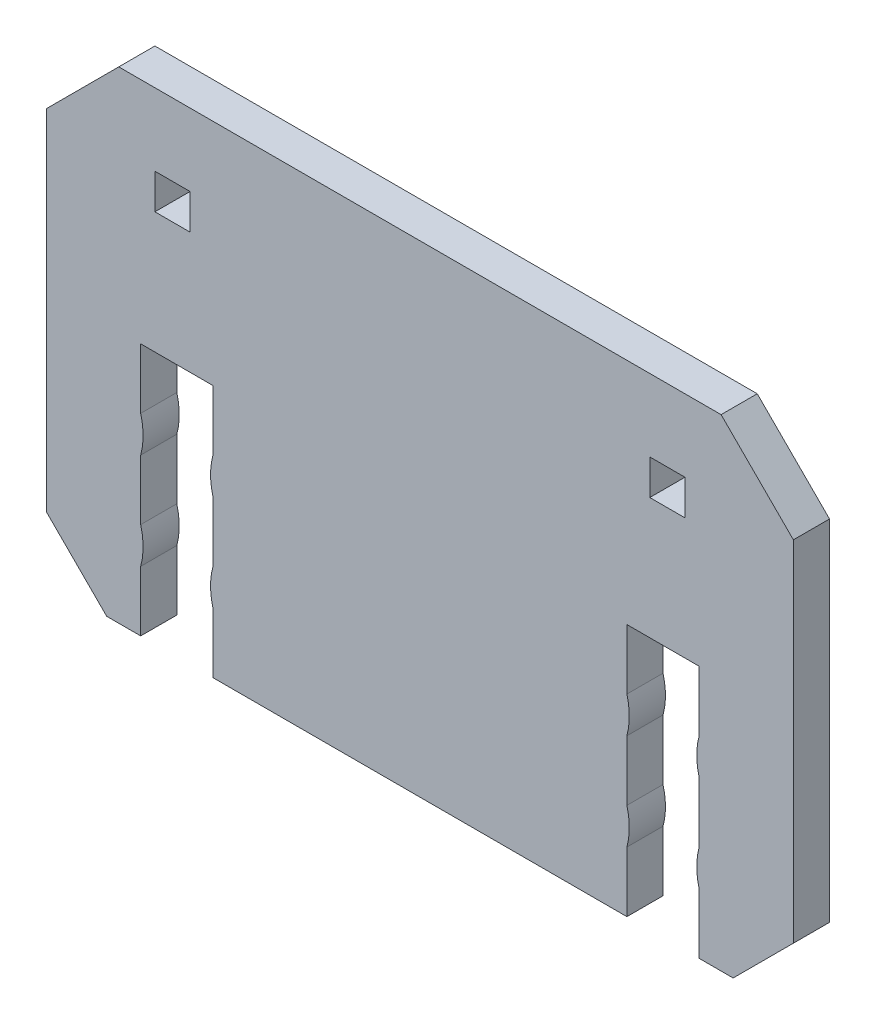
SolidWorks part; units mm, degrees
ref_plane "Front Plane" through (0, 0, 0) normal (0, 0, 1) x (1, 0, 0)
ref_plane "Top Plane" through (0, 0, 0) normal (0, 1, 0) x (1, 0, 0)
ref_plane "Right Plane" through (0, 0, 0) normal (1, 0, 0) x (0, 0, -1)
sketch "Sketch1" plane through (0, 0, 0) normal (0, 0, 1) x (1, 0, 0)
  line L0 (22.1346, 14.538) -> (28.1346, 8.538)
  line L1 (-33.8654, 14.538) -> (28.1346, 14.538)
  line L2 (-33.8654, 14.538) -> (-33.8654, -25.462)
  line L3 (-33.8654, -25.462) -> (28.1346, -25.462)
  line L4 (28.1346, 14.538) -> (28.1346, -25.462)
  line L5 (-2.8654, 14.538) -> (-2.8654, 26.2114) construction
  line L6 (28.1346, -20.462) -> (23.1346, -25.462)
  line L7 (20.3146, -25.462) -> (20.3146, -20.462)
  line L8 (20.3146, -4.462) -> (14.3146, -4.462)
  line L9 (14.3146, -4.462) -> (14.3146, -9.462)
  line L10 (-33.8654, -20.462) -> (-28.8654, -25.462)
  line L11 (16.2146, 8.538) -> (19.1346, 8.538)
  line L12 (16.2146, 8.538) -> (16.2146, 5.618)
  line L13 (16.2146, 5.618) -> (19.1346, 5.618)
  line L14 (19.1346, 8.538) -> (19.1346, 5.618)
  line L15 (-26.0454, -25.462) -> (-26.0454, -20.462)
  line L16 (-26.0454, -4.462) -> (-20.0454, -4.462)
  line L17 (-20.0454, -4.462) -> (-20.0454, -9.462)
  line L18 (-24.8654, 8.538) -> (-24.8654, 5.618)
  line L19 (-21.9454, 5.618) -> (-24.8654, 5.618)
  line L20 (-21.9454, 8.538) -> (-21.9454, 5.618)
  line L21 (-21.9454, 8.538) -> (-24.8654, 8.538)
  line L22 (-27.8654, 14.538) -> (-33.8654, 8.538)
  line L23 (20.1146, -4.9089) -> (20.1146, -24.6398)
  line L24 (23.8617, -9.462) -> (15.6194, -9.462)
  line L25 (24.0542, -12.462) -> (15.6194, -12.462)
  line L26 (23.8617, -17.462) -> (15.6194, -17.462)
  line L27 (23.8617, -20.462) -> (15.6194, -20.462)
  line L28 (17.3146, -6.7173) -> (17.3146, -9.0585) construction
  line L29 (20.3146, -9.462) -> (20.3146, -4.462)
  line L30 (20.3146, -17.462) -> (20.3146, -12.462)
  line L31 (14.3146, -12.462) -> (14.3146, -17.462)
  line L32 (14.3146, -20.462) -> (14.3146, -25.462)
  line L33 (-26.0454, -9.462) -> (-26.0454, -4.462)
  line L34 (-20.0454, -12.462) -> (-20.0454, -17.462)
  line L35 (-26.0454, -17.462) -> (-26.0454, -12.462)
  line L36 (-20.0454, -20.462) -> (-20.0454, -25.462)
  arc A0 (20.3146, -9.462) -> (20.3146, -12.462) centre (25.8396, -10.962) ccw
  arc A1 (20.3146, -20.462) -> (20.3146, -17.462) centre (25.8396, -18.962) cw
  arc A2 (14.3146, -20.462) -> (14.3146, -17.462) centre (8.7896, -18.962) ccw
  arc A3 (14.3146, -9.462) -> (14.3146, -12.462) centre (8.7896, -10.962) cw
  arc A4 (-26.0454, -20.462) -> (-26.0454, -17.462) centre (-31.5704, -18.962) ccw
  arc A5 (-20.0454, -20.462) -> (-20.0454, -17.462) centre (-14.5204, -18.962) cw
  arc A6 (-20.0454, -9.462) -> (-20.0454, -12.462) centre (-14.5204, -10.962) ccw
  arc A7 (-26.0454, -9.462) -> (-26.0454, -12.462) centre (-31.5704, -10.962) cw
  dimension "D1" = 62
  dimension "D2" = 40
  dimension "D3" = 6
  dimension "D4" = 6
  dimension "D5" = 5
  dimension "D6" = 5
  dimension "D7" = 2.82
  dimension "D8" = 6
  dimension "D9" = 21
  dimension "D10" = 2.92
  dimension "D11" = 2.92
  dimension "D12" = 6
  dimension "D13" = 9
  dimension "D14" = 0.2
  dimension "D15" = 5
  dimension "D16" = 5
  dimension "D17" = 3
  dimension "D18" = 3
extrude "Boss-Extrude1" add sketch "Sketch1" along normal blind 3 contours L1 L22 L2 L10 L3 L15 L16 L17 L9 L8 L7 L6 L4 L0 L21 L20 L19 L18 L11 L14 L13 L12
